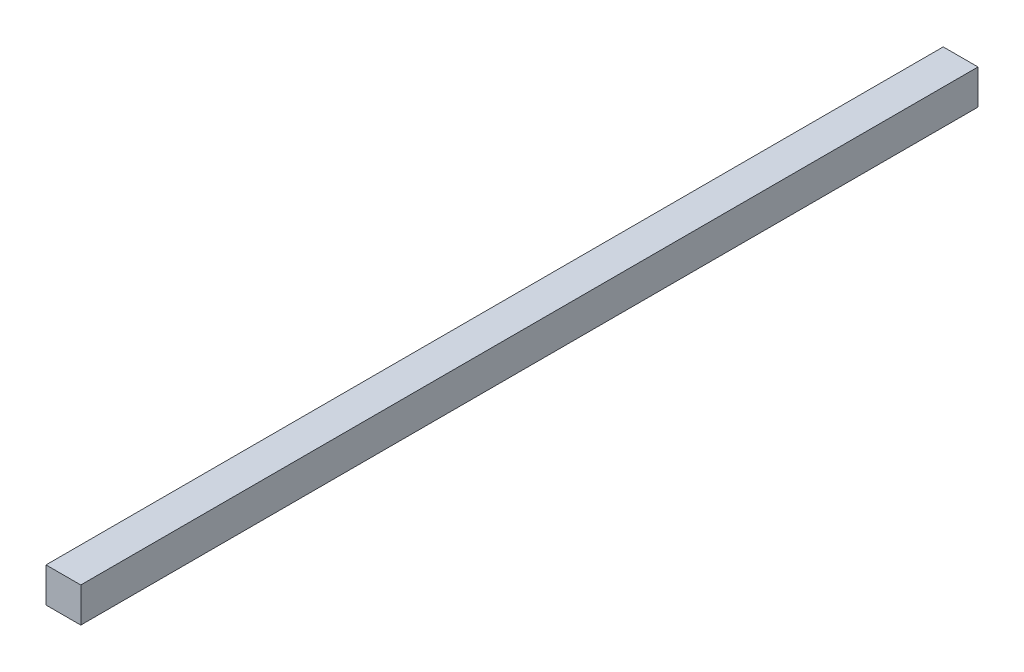
SolidWorks part; units mm, degrees
ref_plane "前视基准面" through (0, 0, 0) normal (0, 0, 1) x (1, 0, 0)
ref_plane "上视基准面" through (0, 0, 0) normal (0, 1, 0) x (1, 0, 0)
ref_plane "右视基准面" through (0, 0, 0) normal (1, 0, 0) x (0, 0, -1)
sketch "草图1" plane through (0, 0, 0) normal (0, 0, 1) x (1, 0, 0)
  line L1 (-3.1633, -1.7398) -> (12.3367, -1.7398)
  line L2 (-3.1633, -1.7398) -> (-3.1633, 13.7602)
  line L3 (-3.1633, 13.7602) -> (12.3367, 13.7602)
  line L4 (12.3367, -1.7398) -> (12.3367, 13.7602)
  dimension "D1" = 15.5
  dimension "D2" = 15.5
extrude "凸台-拉伸1" add sketch "草图1" along normal blind 400
